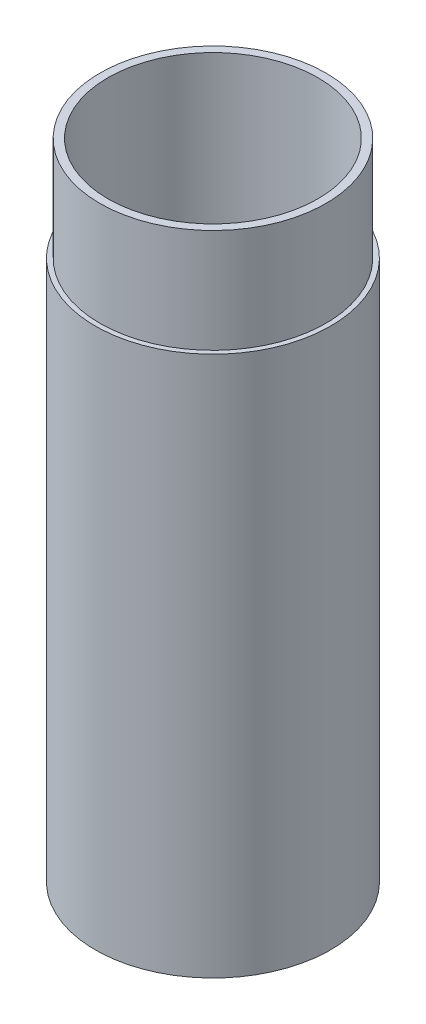
SolidWorks part; units mm, degrees
material "ABS"
ref_plane "前视基准面" through (0, 0, 0) normal (0, 0, 1) x (1, 0, 0)
ref_plane "上视基准面" through (0, 0, 0) normal (0, 1, 0) x (1, 0, 0)
ref_plane "右视基准面" through (0, 0, 0) normal (1, 0, 0) x (0, 0, -1)
other "Configuration Table"
sketch "草图1" plane through (0, 0, 0) normal (0, 1, 0) x (1, 0, 0)
  circle A0 centre (0, 0) radius 22.25
  circle A1 centre (0, 0) radius 24.95
  dimension "D1" = 44.5
  dimension "D2" = 49.9
extrude "凸台-拉伸1" add sketch "草图1" along normal blind 114.5
sketch "草图2" plane through (0, 114.5, 0) normal (0, 1, 0) x (1, 0, 0)
  circle A0 centre (0, 0) radius 23.95
  circle A1 centre (0, 0) radius 22.25 construction
  circle A2 centre (0, 0) radius 22.25
  dimension "D1" = 47.9
extrude "凸台-拉伸2" add sketch "草图2" along normal blind 22
chamfer "倒角1" distance 1 angle 45 1 edges at (0, 0, 22.25)
fillet "圆角1" radius 1 2 edges at (0, 0, 23.25) (0, 1, 22.25)
